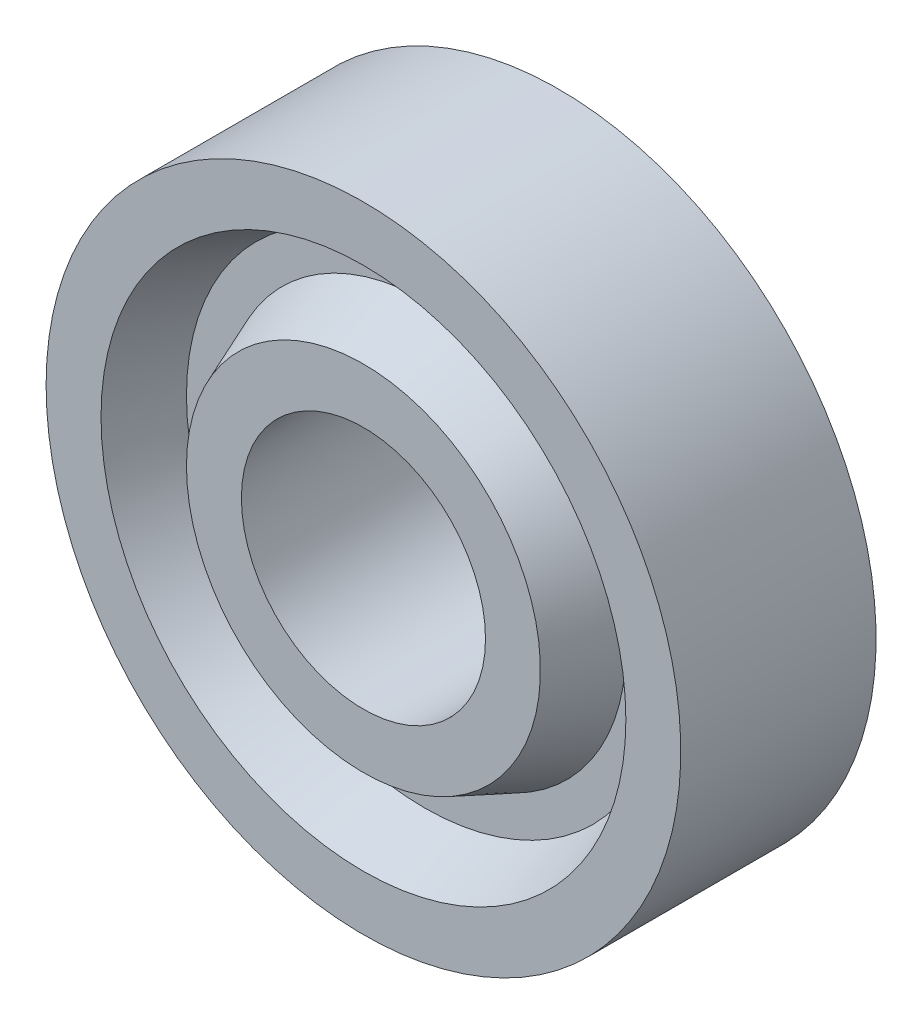
SolidWorks part; units mm, degrees
ref_plane "Front Plane" through (0, 0, 0) normal (0, 0, 1) x (1, 0, 0)
ref_plane "Top Plane" through (0, 0, 0) normal (0, 1, 0) x (1, 0, 0)
ref_plane "Right Plane" through (0, 0, 0) normal (1, 0, 0) x (0, 0, -1)
sketch "Sketch1" plane through (0, 0, 0) normal (0, 1, 0) x (1, 0, 0)
  line L0 (0, 28.9111) -> (0, -36.6207) construction
  line L2 (7.25, 4) -> (8.25, 1.5)
  line L3 (8.25, 1.5) -> (9.75, 1.5)
  line L4 (9.75, 1.5) -> (10.75, 4)
  line L6 (13, 4) -> (13, -4)
  line L8 (10.75, -4) -> (9.75, -1.5)
  line L9 (9.75, -1.5) -> (8.25, -1.5)
  line L10 (8.25, -1.5) -> (7.25, -4)
  line L12 (5, -4) -> (5, 4)
  line L13 (0, 0) -> (5, 0) construction
  line L14 (8.25, -1.5) -> (8.25, 1.5) construction
  line L15 (9.75, -1.5) -> (9.75, 1.5) construction
  line L16 (5, 4) -> (7.25, 4)
  line L17 (10.75, 4) -> (13, 4)
  line L18 (10.75, -4) -> (13, -4)
  line L19 (5, -4) -> (7.25, -4)
  line L20 (7.25, -4) -> (10.75, -4) construction
  line L21 (7.25, 4) -> (10.75, 4) construction
  line L22 (7.25, -4) -> (7.25, 4) construction
  line L23 (10.75, -4) -> (10.75, 4) construction
  dimension "D1" = 5
  dimension "D2" = 13
  dimension "D3" = 3.5
  dimension "D5" = 2.5
  dimension "D6" = 8
  dimension "D7" = 1.5
revolve "Revolve1" add sketch "Sketch1" angle 360 about L0
